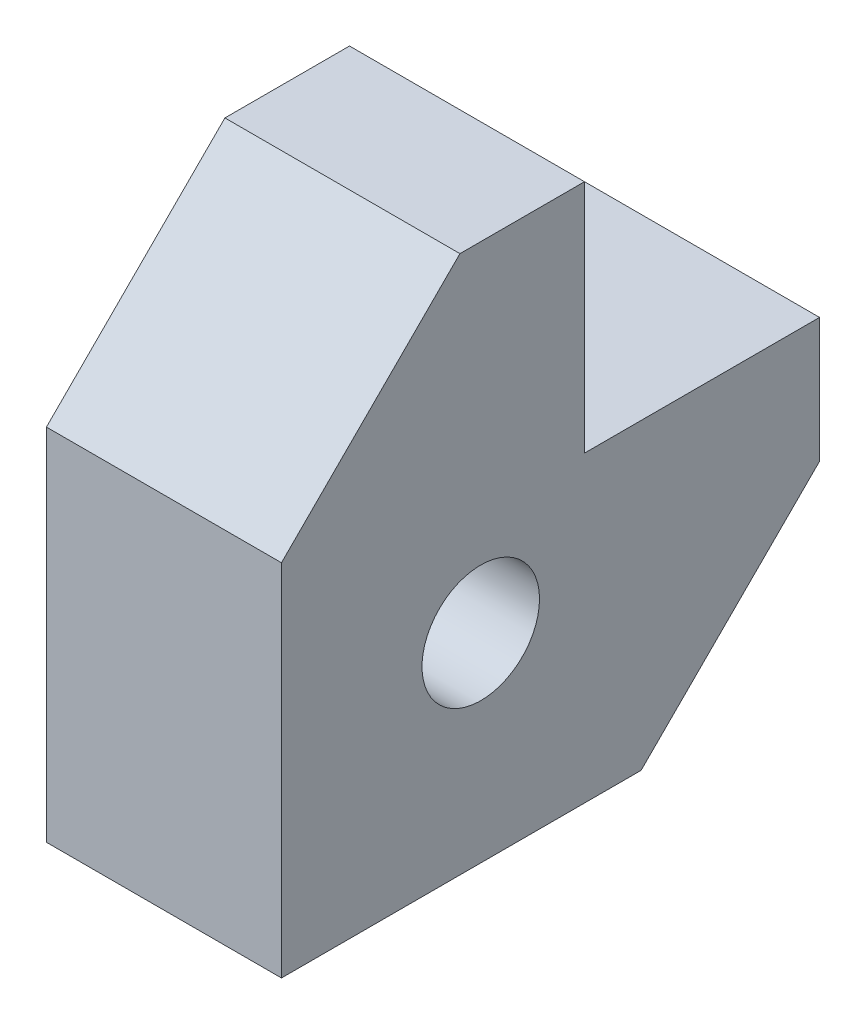
SolidWorks part; units mm, degrees
ref_plane "Front" through (0, 0, 0) normal (0, 0, 1) x (1, 0, 0)
ref_plane "Top" through (0, 0, 0) normal (0, 1, 0) x (1, 0, 0)
ref_plane "Right" through (0, 0, 0) normal (1, 0, 0) x (0, 0, -1)
sketch "Skizze1" plane through (0, 0, 0) normal (1, 0, 0) x (0, 0, -1)
  line L0 (0, 0) -> (0, 20)
  line L1 (0, 0) -> (20, 0)
  line L2 (0, 20) -> (-10.601, 20)
  line L3 (0, 0) -> (-43.3653, -43.3653) construction
  line L4 (-10.601, 20) -> (-25.7877, 4.8133)
  line L5 (-25.7877, 4.8133) -> (-25.7877, -25.7877)
  line L6 (20, 0) -> (20, -10.601)
  line L7 (20, -10.601) -> (4.8133, -25.7877)
  line L8 (4.8133, -25.7877) -> (-25.7877, -25.7877)
  circle A0 centre (-8.8301, -8.8301) radius 5
  dimension "D2" = 10
  dimension "D1" = 20
extrude "Aufsatz-Linear austragen1" add sketch "Skizze1" along normal blind 20
